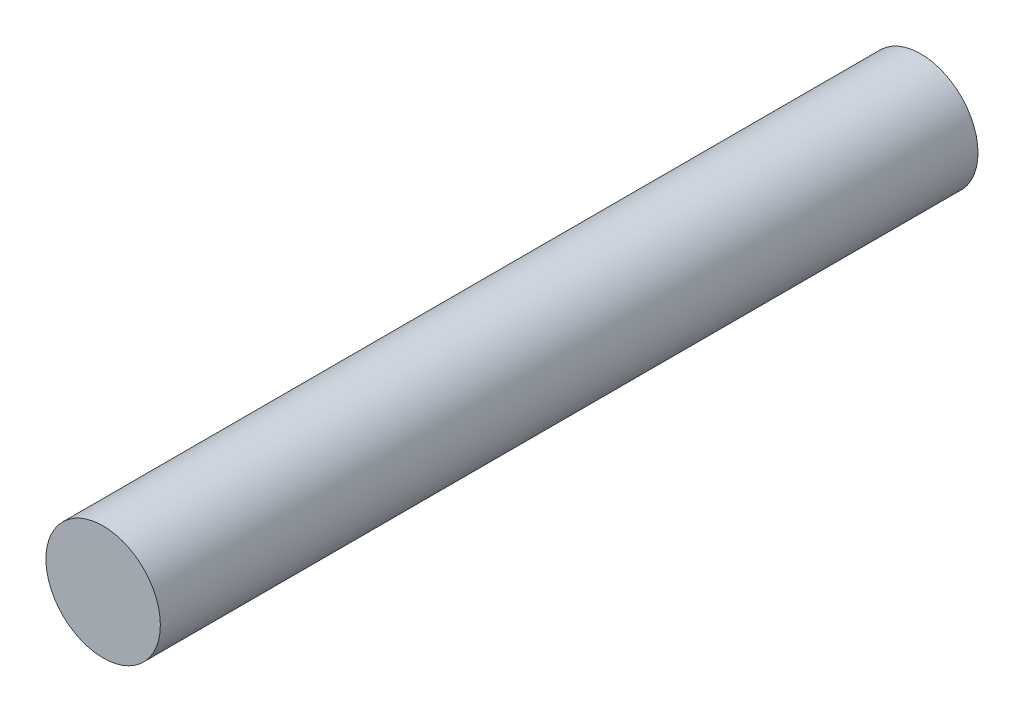
SolidWorks part; units mm, degrees
ref_plane "Front Plane" through (0, 0, 0) normal (0, 0, 1) x (1, 0, 0)
ref_plane "Top Plane" through (0, 0, 0) normal (0, 1, 0) x (1, 0, 0)
ref_plane "Right Plane" through (0, 0, 0) normal (1, 0, 0) x (0, 0, -1)
sketch "Sketch1" plane through (0, 0, 0) normal (0, 0, 1) x (1, 0, 0)
  circle A0 centre (0, 0) radius 7
  dimension "D1" = 14
extrude "Boss-Extrude1" add sketch "Sketch1" along normal blind 100
